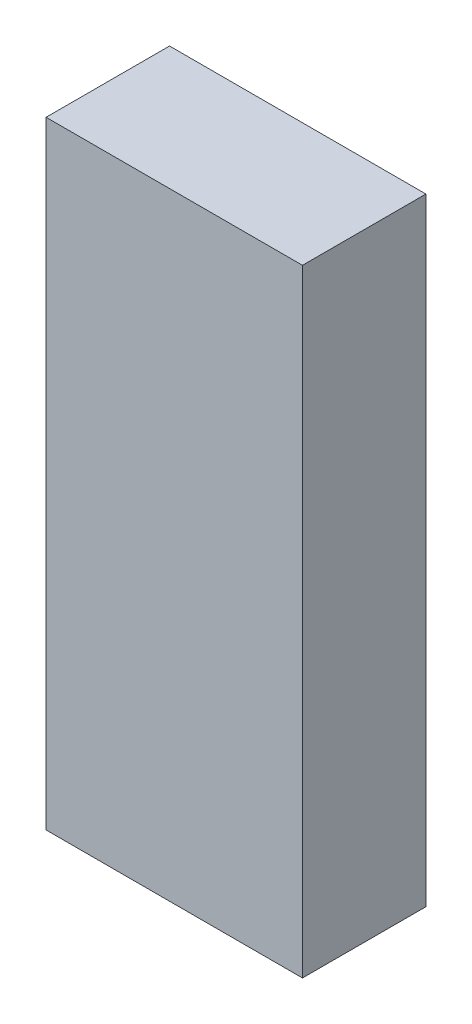
SolidWorks part; units mm, degrees
ref_plane "Plan de face" through (0, 0, 0) normal (0, 0, 1) x (1, 0, 0)
ref_plane "Plan de dessus" through (0, 0, 0) normal (0, 1, 0) x (1, 0, 0)
ref_plane "Plan de droite" through (0, 0, 0) normal (1, 0, 0) x (0, 0, -1)
sketch "Esquisse1" plane through (0, 0, 0) normal (0, 0, 1) x (1, 0, 0)
  line L1 (-13.5, -32.5) -> (13.5, -32.5)
  line L2 (-13.5, -32.5) -> (-13.5, 32.5)
  line L3 (-13.5, 32.5) -> (13.5, 32.5)
  line L4 (13.5, -32.5) -> (13.5, 32.5)
  line L5 (-13.5, -32.5) -> (13.5, 32.5) construction
  line L6 (-13.5, 32.5) -> (13.5, -32.5) construction
  point P0 (0, 0)
  dimension "D1" = 27
  dimension "D2" = 65
extrude "Boss.-Extru.1" add sketch "Esquisse1" along normal mid plane 13
